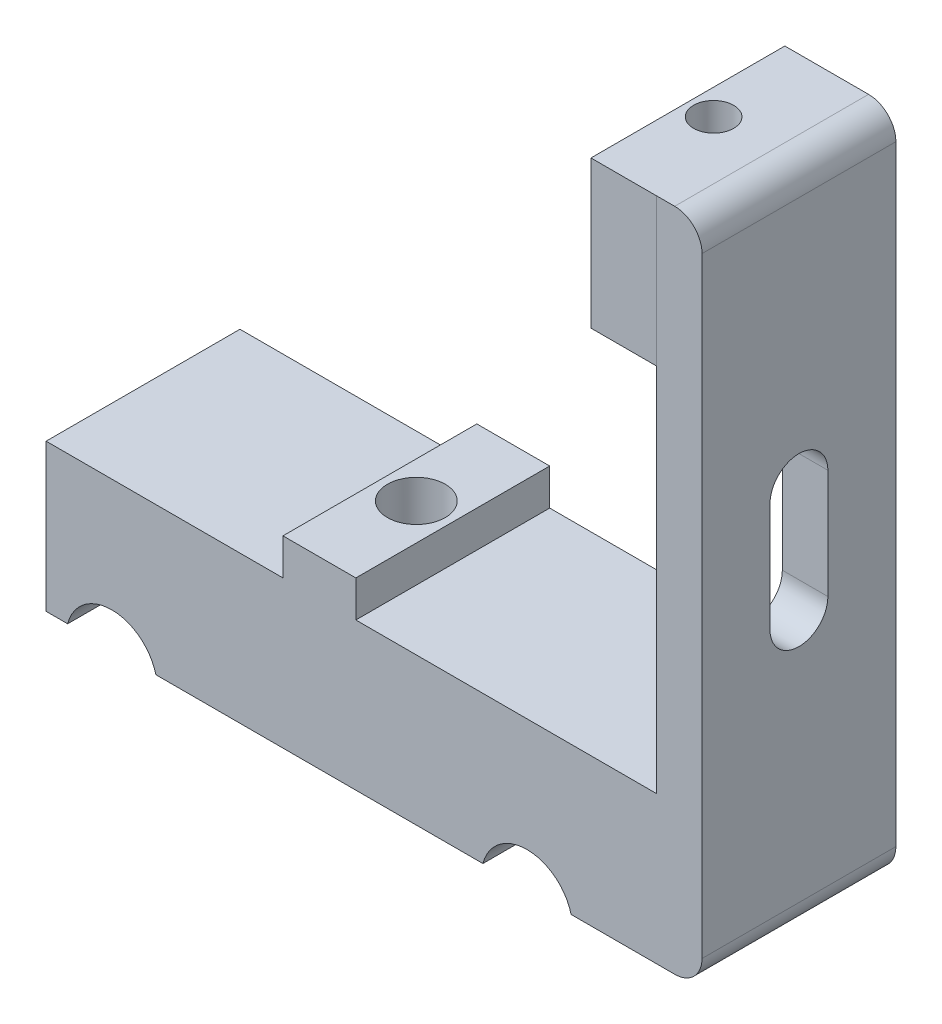
SolidWorks part; units mm, degrees
ref_plane "Front Plane" through (0, 0, 0) normal (0, 0, 1) x (1, 0, 0)
ref_plane "Top Plane" through (0, 0, 0) normal (0, 1, 0) x (1, 0, 0)
ref_plane "Right Plane" through (0, 0, 0) normal (1, 0, 0) x (0, 0, -1)
sketch "Sketch2" plane through (0, 0, 0) normal (0, 0, 1) x (1, 0, 0)
  line L0 (10.1, 0) -> (-10.1, 0)
  line L1 (-10.1, 0) -> (-10.1, 1.7099)
  line L2 (-10.1, 1.7099) -> (-6.2548, 7)
  line L3 (-6.2548, 7) -> (6.2548, 7)
  line L4 (0, 7) -> (0, 0)
  line L5 (0, 0) -> (0, 9.2516) construction
  line L6 (10.1, 1.7099) -> (6.2548, 7)
  line L7 (10.1, 0) -> (10.1, 1.7099)
  dimension "D1" = 20.2
  dimension "D2" = 7
extrude "Boss-Extrude1" add sketch "Sketch2" along normal blind 10.8 contours L4 L3 L2 L1 L0 | L0 L7 L6 L3 L4
sketch "Sketch4" plane through (0, 0, 0) normal (0, 0, 1) x (1, 0, 0)
  line L0 (-4, 0) -> (-4, -4.8)
  line L1 (10.1, 0) -> (-10.1, 0) construction
  line L2 (-4, -4.8) -> (-30, -4.8)
  line L3 (-30, -4.8) -> (-30, -29.8)
  line L4 (-30, -29.8) -> (30, -29.8)
  line L5 (0, 0) -> (0, -29.8) construction
  line L6 (0, -29.8) -> (0, 0)
  line L7 (4, 0) -> (-4, 0)
  line L8 (0, 0) -> (0, -30.5381) construction
  line L9 (30, -4.8) -> (30, -29.8)
  line L10 (4, -4.8) -> (30, -4.8)
  line L11 (4, 0) -> (4, -4.8)
  line L13 (-30, -20.98) -> (30, -20.98)
  line L14 (-30, -20.98) -> (-30, -23.48)
  line L15 (-30, -23.48) -> (30, -23.48)
  line L16 (30, -20.98) -> (30, -23.48)
  dimension "D1" = 4.8
  dimension "D2" = 4
  dimension "D3" = 25
  dimension "D4" = 60
  dimension "D6" = 8.82
extrude "Boss-Extrude2" add sketch "Sketch4" along normal mid plane 21.28 contours L6 L7 L0 L2 L3 L4 | L11 L7 L6 L4 L9 L10
sketch "Sketch5" plane through (0, 0, 0) normal (0, 0, 1) x (1, 0, 0)
  line L0 (-29.791, -22.2274) -> (26.9734, -22.2274) construction
  line L3 (0, -20.98) -> (0, 7) construction
  line L5 (-6.2548, 7) -> (6.2548, 7) construction
  line L20 (-30, -20.98) -> (30, -20.98) construction
  circle A0 centre (-22.791, -22.2274) radius 5
  circle A1 centre (22.791, -22.2274) radius 5
  dimension "D1" = 7
extrude "Cut-Extrude1" cut sketch "Sketch5" along normal through all both and the other way through all
fillet "Fillet1" radius 1 6 edges at (-10.1, 0, 5.4) (-10.1, 1.7099, 5.4) (-6.2548, 7, 5.4) (6.2548, 7, 5.4) (10.1, 0, 5.4) (10.1, 1.7099, 5.4)
sketch "Sketch6" plane through (30, 0, 0) normal (1, 0, 0) x (0, 0, -1)
  line L0 (-10.64, -20.98) -> (10.64, -20.98) construction
  line L1 (-10.64, -4.8) -> (10.64, -4.8)
  line L2 (-10.64, -4.8) -> (-10.64, -20.98)
  line L3 (-10.64, -20.98) -> (10.64, -20.98)
  line L4 (10.64, -4.8) -> (10.64, -20.98)
extrude "Boss-Extrude3" add sketch "Sketch6" along normal blind 12
sketch "Sketch7" plane through (0, -4.8, 0) normal (0, 1, 0) x (1, 0, 0)
  line L0 (4, -10.64) -> (42, -10.64) construction
  line L1 (42, 10.6413) -> (37, 10.6413)
  line L2 (42, 10.6413) -> (42, -10.64)
  line L3 (42, -10.64) -> (37, -10.64)
  line L4 (37, 10.6413) -> (37, -10.64)
  dimension "D1" = 5
extrude "Boss-Extrude4" add sketch "Sketch7" along normal blind 56.83
sketch "Sketch8" plane through (37, 0, 0) normal (-1, 0, 0) x (0, 0, 1)
  line L0 (-10.6413, 52.03) -> (-10.6413, -4.8) construction
  line L1 (10.643, 52.03) -> (-10.6413, 52.03)
  line L2 (10.643, 52.03) -> (10.643, 35.85)
  line L3 (10.643, 35.85) -> (-10.6413, 35.85)
  line L4 (-10.6413, 52.03) -> (-10.6413, 35.85)
  dimension "D1" = 16.18
extrude "Boss-Extrude5" add sketch "Sketch8" along normal blind 7.19
fillet "Fillet3" radius 3 2 edges at (42, 52.03, -0.0007) (42, -20.98, 0)
sketch "Sketch9" plane through (0, -20.98, 0) normal (0, -1, 0) x (1, 0, 0)
  line L0 (27.6329, 0) -> (27.6329, 10.8) construction
  line L2 (27.6329, 10.64) -> (39, 10.64) construction
  circle A0 centre (32.6329, 0) radius 2.2
  dimension "D1" = 5
  dimension "D2" = 10.64
extrude "Cut-Extrude2" cut sketch "Sketch9" against normal through all
sketch "Sketch10" plane through (0, -20.98, 0) normal (0, -1, 0) x (1, 0, 0)
  line L2 (-17.9491, 0) -> (-17.9491, 10.8) construction
  line L3 (-17.9491, 10.64) -> (17.9491, 10.64) construction
  circle A0 centre (0.0009, 0) radius 3.175
  dimension "D1" = 10.64
  dimension "D2" = 17.95
extrude "Cut-Extrude3" cut sketch "Sketch10" against normal through all
sketch "Sketch11" plane through (0, 0, 10.8) normal (0, 0, 1) x (1, 0, 0)
  line L0 (9.1, 0) -> (-9.1, 0) construction
  line L1 (-12.6098, 8.9215) -> (12.3675, 8.9215)
  line L2 (-12.6098, 8.9215) -> (-12.6098, -0.8)
  line L3 (-12.6098, -0.8) -> (12.3675, -0.8)
  line L4 (12.3675, 8.9215) -> (12.3675, -0.8)
  dimension "D1" = 0.8
extrude "Cut-Extrude4" cut sketch "Sketch11" against normal through all
sketch "Sketch12" plane through (0, -20.98, 0) normal (0, -1, 0) x (1, 0, 0)
  arc A0 (-8.6262, 5.538) -> (-6.6262, 5.538) centre (-7.6262, 5.538) ccw construction
  arc A1 (-6.6262, 5.538) -> (-8.6262, 5.538) centre (-7.6262, 5.538) ccw construction
  arc A2 (-15.1262, 5.538) -> (-13.1262, 5.538) centre (-14.1262, 5.538) ccw construction
  arc A3 (-13.1262, 5.538) -> (-15.1262, 5.538) centre (-14.1262, 5.538) ccw construction
  arc A4 (-8.6262, 5.538) -> (-6.6262, 5.538) centre (-7.6262, 5.538) ccw
  arc A5 (-6.6262, 5.538) -> (-8.6262, 5.538) centre (-7.6262, 5.538) ccw
  arc A6 (-15.1262, 5.538) -> (-13.1262, 5.538) centre (-14.1262, 5.538) ccw
  arc A7 (-13.1262, 5.538) -> (-15.1262, 5.538) centre (-14.1262, 5.538) ccw
extrude "Cut-Extrude5" [suppressed] cut sketch "Sketch12" against normal up to next
sketch "Sketch13" plane through (42, 0, 0) normal (1, 0, 0) x (0, 0, -1)
  line L0 (10.6413, 49.03) -> (-10.64, 49.03) construction
  line L1 (3.175, 21.525) -> (3.175, 9.525)
  line L2 (-3.175, 21.525) -> (-3.175, 9.525)
  arc A0 (3.175, 21.525) -> (-3.175, 21.525) centre (0, 21.525) ccw
  arc A1 (-3.175, 9.525) -> (3.175, 9.525) centre (0, 9.525) ccw
  dimension "D1" = 27.505
  dimension "D2" = 12
extrude "Cut-Extrude6" cut sketch "Sketch13" against normal through all
